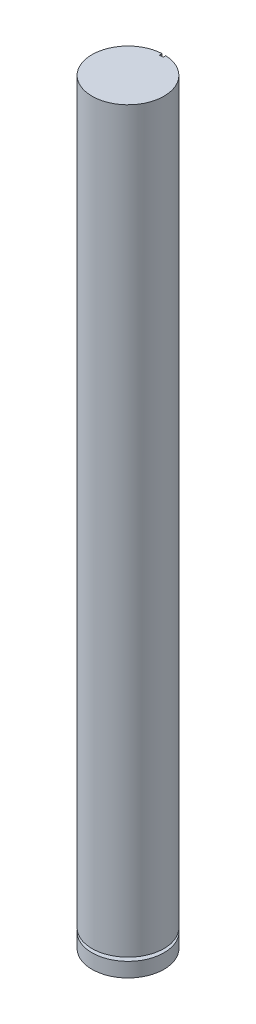
SolidWorks part; units mm, degrees
ref_plane "Front Plane" through (0, 0, 0) normal (0, 0, 1) x (1, 0, 0)
ref_plane "Top Plane" through (0, 0, 0) normal (0, 1, 0) x (1, 0, 0)
ref_plane "Right Plane" through (0, 0, 0) normal (1, 0, 0) x (0, 0, -1)
sketch "Sketch1" plane through (0, 0, 0) normal (0, 1, 0) x (1, 0, 0)
  circle A0 centre (0, 0) radius 2
  dimension "D1" = 4
extrude "Boss-Extrude1" add sketch "Sketch1" along normal blind 42
sketch "Sketch2" plane through (0, 0, 0) normal (1, 0, 0) x (0, 0, -1)
  line L0 (2, 0) -> (2, 42) construction
  line L1 (2, 1) -> (1.5, 1)
  line L2 (2, 1) -> (2, 0.8)
  line L3 (2, 0.8) -> (1.5, 0.8)
  line L4 (1.5, 1) -> (1.5, 0.8)
  line L5 (-2, 0) -> (2, 0) construction
  line L6 (0, 0) -> (0, 1.4139) construction
  dimension "D1" = 0.2
  dimension "D2" = 0.5
  dimension "D3" = 0.8
revolve "Cut-Revolve1" cut sketch "Sketch2" angle 360 about L6
sketch "Sketch3" plane through (0, 42, 0) normal (0, 1, 0) x (1, 0, 0)
  line L0 (0, 0) -> (0, 2) construction
  line L2 (-0.1, 2) -> (0.1, 2)
  line L3 (-0.1, 2) -> (-0.1, 1.85)
  line L4 (-0.1, 1.85) -> (0.1, 1.85)
  line L5 (0.1, 2) -> (0.1, 1.85)
  circle A0 centre (0, 0) radius 2 construction
  dimension "D1" = 0.2
  dimension "D2" = 0.15
extrude "Cut-Extrude1" cut sketch "Sketch3" against normal blind 3
